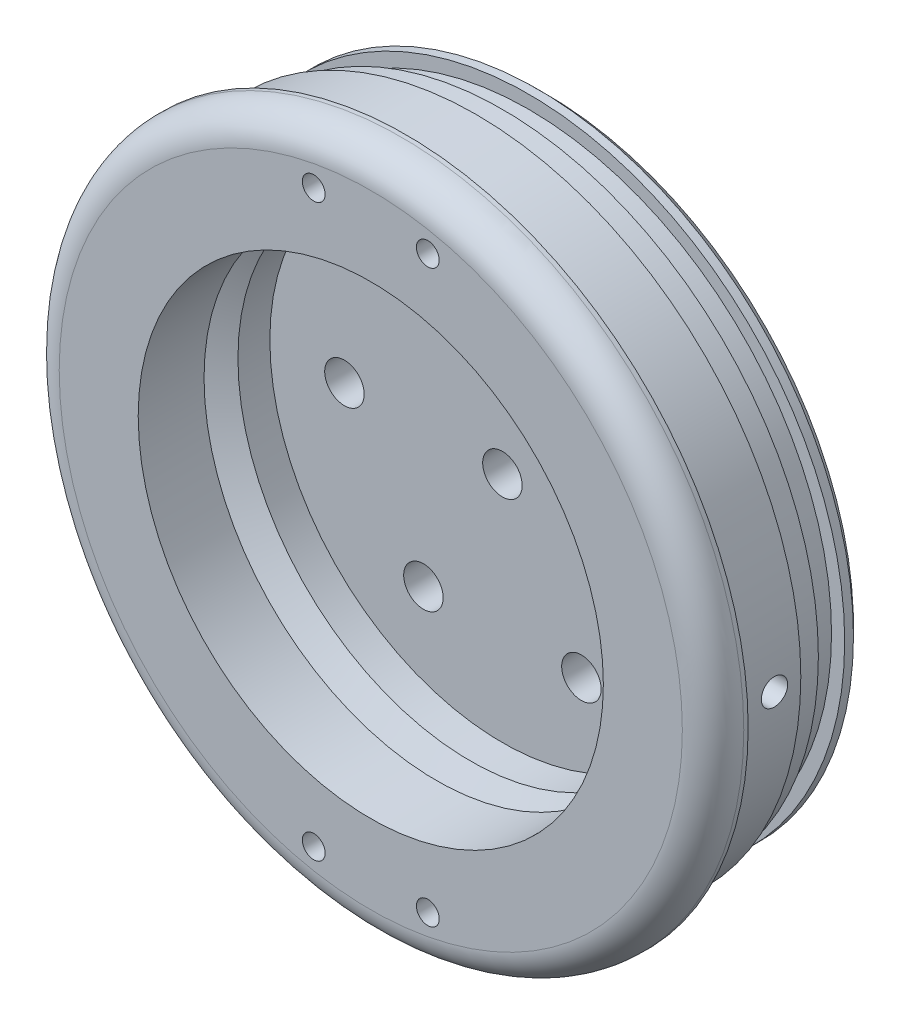
SolidWorks part; units mm, degrees
ref_plane "Спереди" through (0, 0, 0) normal (0, 0, 1) x (1, 0, 0)
ref_plane "Сверху" through (0, 0, 0) normal (0, 1, 0) x (1, 0, 0)
ref_plane "Справа" through (0, 0, 0) normal (1, 0, 0) x (0, 0, -1)
sketch "Эскиз1" plane through (0, 0, 0) normal (0, 0, 1) x (1, 0, 0)
  circle A0 centre (0, 0) radius 39
  dimension "D1" = 78
extrude "Бобышка-Вытянуть1" add sketch "Эскиз1" along normal blind 4
sketch "Эскиз2" plane through (0, 0, 4) normal (0, 0, 1) x (1, 0, 0)
  line L0 (0, 40.548) -> (0, -43.3588) construction
fillet "Скругление1" radius 3.5 1 edges at (39, 0, 4)
sketch "Эскиз3" plane through (0, 0, 0) normal (0, 0, -1) x (-1, 0, 0)
  circle A0 centre (0, 0) radius 37
  dimension "D1" = 74
extrude "Бобышка-Вытянуть2" add sketch "Эскиз3" along normal blind 8
sketch "Эскиз4" plane through (0, 0, -8) normal (0, 0, -1) x (-1, 0, 0)
  circle A0 centre (0, 0) radius 36
  dimension "D1" = 72
extrude "Бобышка-Вытянуть3" add sketch "Эскиз4" along normal blind 8
sketch "Эскиз5" plane through (0, 0, 0) normal (1, 0, 0) x (0, 0, -1)
  line L0 (-46.651, 0) -> (48.0815, 0) construction
  line L1 (16, 36) -> (8, 36) construction
  line L2 (14, 36) -> (11, 36)
  line L3 (14, 36) -> (14, 34.5)
  line L4 (14, 34.5) -> (11, 34.5)
  line L5 (11, 36) -> (11, 34.5)
  line L6 (16, -36) -> (16, 36) construction
  dimension "D1" = 2
  dimension "D2" = 1.5
  dimension "D3" = 3
revolve "Вырез-Повернуть1" cut sketch "Эскиз5" angle 360 about L0
sketch "Эскиз7" plane through (0, 0, -16) normal (0, 0, -1) x (-1, 0, 0)
  circle A0 centre (0, 0) radius 27
  dimension "D1" = 54
extrude "Вырез-Вытянуть1" cut sketch "Эскиз7" against normal blind 17
chamfer "Фаска2" distance 1 angle 45 1 edges at (-36, 0, -16)
ref_plane "Плоскость6" [suppressed] through (37, 0, 0) normal (1, 0, 0) x (0, 0, -1)
sketch "Эскиз14" [suppressed] plane through (37, 0, 0) normal (1, 0, 0) x (0, 0, -1)
  line L0 (0, 0) -> (8.9796, 0) construction
  line L1 (8, -37) -> (8, 37) construction
  circle A0 centre (5, 0) radius 1.3
  dimension "D2" = 2.6
  dimension "D1" = 3
extrude "Вырез-Вытянуть4" [suppressed] cut sketch "Эскиз14" against normal blind 7
ref_plane "Плоскость7" [suppressed] through (-37, 0, 0) normal (1, 0, 0) x (0, 0, -1)
sketch "Эскиз16" [suppressed] plane through (-37, 0, 0) normal (1, 0, 0) x (0, 0, -1)
  line L0 (0, 0) -> (13.6916, 0) construction
  line L1 (8, -36) -> (8, 36) construction
  circle A0 centre (5, 0) radius 1.3
  dimension "D2" = 2.6
  dimension "D1" = 3
extrude "Вырез-Вытянуть5" [suppressed] cut sketch "Эскиз16" along normal blind 7
thread "Резьба1" [suppressed] pitch 0.3 start angle 0, offset 0, length 7, pitch 0.3, diameter 2.6
ref_plane "Плоскость8" through (37, 0, -3.7) normal (0, -1, 0) x (0, 0, 1)
sketch "Профиль резьбы1" plane through (37, 0, -3.7) normal (0, -1, 0) x (0, 0, 1)
  line L0 (0, 0) -> (0, 0.3) construction
  line L11 (0, 0.2625) -> (0, 0)
  line L12 (0, 0) -> (0.1624, 0.0938)
  line L13 (0.1624, 0.0938) -> (0.1624, 0.1688)
  line L15 (0.1624, 0.1688) -> (0, 0.2625)
  line L17 (0.1624, 0.1313) -> (0, 0.1313) construction
  point P3 (0, 0)
  dimension "Pitch" = 0.3
  dimension "Profile_Angle" = 60
  dimension "Profile_Land" = 0.075
  dimension "Profile_Height" = 0.1624
thread "Резьба2" [suppressed] pitch 0.3 start angle 0, offset 0, length 7, pitch 0.3, diameter 2.6
ref_plane "Плоскость9" through (-37, 0, -6.3) normal (0, -1, 0) x (0, 0, -1)
sketch "Профиль резьбы2" plane through (-37, 0, -6.3) normal (0, -1, 0) x (0, 0, -1)
  line L0 (0, 0) -> (0, 0.3) construction
  line L11 (0, 0.2625) -> (0, 0)
  line L12 (0, 0) -> (0.1624, 0.0938)
  line L13 (0.1624, 0.0938) -> (0.1624, 0.1688)
  line L15 (0.1624, 0.1688) -> (0, 0.2625)
  line L17 (0.1624, 0.1313) -> (0, 0.1313) construction
  point P3 (0, 0)
  dimension "Pitch" = 0.3
  dimension "Profile_Angle" = 60
  dimension "Profile_Land" = 0.075
  dimension "Profile_Height" = 0.1624
sketch "Эскиз18" plane through (0, 0, 4) normal (0, 0, 1) x (1, 0, 0)
  line L0 (0, 32.5) -> (12.4261, 32.5) construction
  line L1 (0, 46.4307) -> (0, -52.0425) construction
  line L2 (-51.6992, 0) -> (67.4175, 0) construction
  circle A0 centre (6.5, 32.5) radius 1.3
  circle A1 centre (-6.5, 32.5) radius 1.3
  circle A2 centre (6.5, -32.5) radius 1.3
  circle A3 centre (-6.5, -32.5) radius 1.3
  dimension "D1" = 2.6
  dimension "D2" = 6.5
extrude "Вырез-Вытянуть6" cut sketch "Эскиз18" against normal blind 7
sketch "Эскиз19" plane through (0, 0, 1) normal (0, 0, -1) x (-1, 0, 0)
  circle A0 centre (0, 0) radius 27
extrude "Бобышка-Вытянуть4" add sketch "Эскиз19" along normal blind 17
sketch "Эскиз20" plane through (0, 0, 4) normal (0, 0, 1) x (1, 0, 0)
  circle A0 centre (0, 0) radius 26.5
  dimension "D1" = 53
extrude "Вырез-Вытянуть7" cut sketch "Эскиз20" against normal blind 15
sketch "Эскиз21" plane through (0, 0, -11) normal (0, 0, 1) x (1, 0, 0)
  circle A1 centre (-18, 0) radius 2.25
  circle A2 centre (-9, 15.5885) radius 2.25
  circle A3 centre (9, 15.5885) radius 2.25
  circle A4 centre (18, 0) radius 2.25
  circle A5 centre (9, -15.5885) radius 2.25
  circle A6 centre (-9, -15.5885) radius 2.25
  circle A7 centre (0, 0) radius 2.25
  point P20 (0, 0)
  dimension "D2" = 4.5
  dimension "D4" = 4.5
  dimension "D3" = 6
extrude "Вырез-Вытянуть8" cut sketch "Эскиз21" against normal blind 15
sketch "Эскиз22" plane through (0, 0, 0) normal (1, 0, 0) x (0, 0, -1)
  line L0 (-32.0056, 0) -> (47.7052, 0) construction
  line L1 (3.5, 26.5) -> (5.3834, 29.8175)
  line L2 (11, 26.5) -> (-4, 26.5) construction
  line L3 (5.3834, 29.8175) -> (7.3635, 26.5)
  line L4 (7.3635, 26.5) -> (3.5, 26.5)
revolve "Вырез-Повернуть2" cut sketch "Эскиз22" angle 360 about L0
sketch "Эскиз23" plane through (0, 0, -16) normal (0, 0, -1) x (-1, 0, 0)
  line L0 (0, 0) -> (-47.0865, 0) construction
  line L1 (0, 40.548) -> (0, -5.6095) construction
  line L2 (0, 40.548) -> (0, -43.3588) construction
  line L3 (-15.8507, 22.0606) -> (23.6591, 22.0606) construction
  circle A2 centre (23.1804, 22.0606) radius 1.3
  circle A3 centre (-23.1804, 22.0606) radius 1.3
  circle A4 centre (23.1804, -22.0606) radius 1.3
  circle A5 centre (-23.1804, -22.0606) radius 1.3
  point P13 (0, 36.0606)
  dimension "D2" = 14
  dimension "D3" = 2.6
extrude "Вырез-Вытянуть9" cut sketch "Эскиз23" against normal blind 7
sketch "Эскиз25" plane through (0, 0, 0) normal (1, 0, 0) x (0, 0, -1)
  line L0 (0, 0) -> (50000, 0) construction
  line L1 (0, -39) -> (0, 39) construction
  circle A0 centre (5, 0) radius 1.5
  dimension "D1" = 3
  dimension "D2" = 5
extrude "Вырез-Вытянуть11" cut sketch "Эскиз25" against normal blind 4 from offset 38
pattern_circular "Круговой массив2" count 2 over 360 about axis through (0, 0, -8) along (0, 0, 1) of "Вырез-Вытянуть11"
